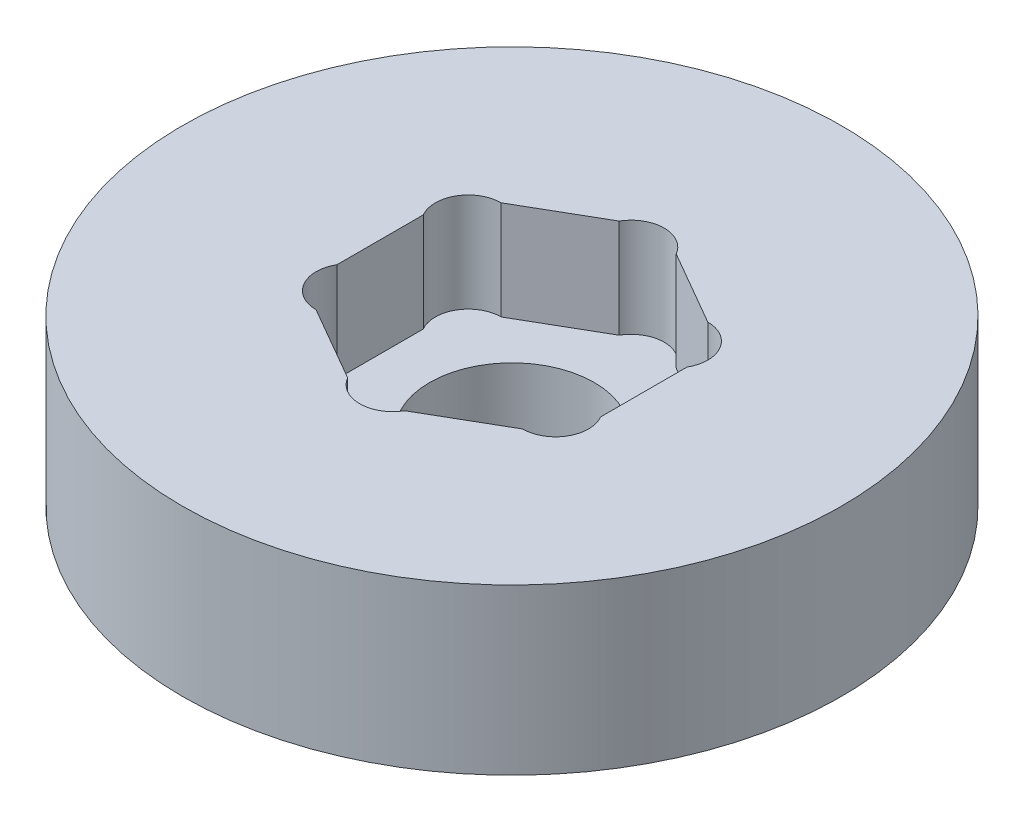
SolidWorks part; units mm, degrees
ref_plane "정면" through (0, 0, 0) normal (0, 0, 1) x (1, 0, 0)
ref_plane "윗면" through (0, 0, 0) normal (0, 1, 0) x (1, 0, 0)
ref_plane "우측면" through (0, 0, 0) normal (1, 0, 0) x (0, 0, -1)
sketch "스케치1" plane through (0, 0, 0) normal (0, 1, 0) x (1, 0, 0)
  circle A0 centre (0, 0) radius 10
  dimension "D1" = 20
extrude "보스-돌출1" add sketch "스케치1" along normal blind 5
sketch "스케치2" plane through (0, 5, 0) normal (0, 1, 0) x (1, 0, 0)
  line L1 (0, 4.6188) -> (-4, 2.3094)
  line L2 (-4, 2.3094) -> (-4, -2.3094)
  line L3 (-4, -2.3094) -> (0, -4.6188)
  line L4 (0, -4.6188) -> (4, -2.3094)
  line L5 (4, -2.3094) -> (4, 2.3094)
  line L6 (4, 2.3094) -> (0, 4.6188)
  circle A0 centre (0, 0) radius 4 construction
  dimension "D1" = 8
extrude "컷-돌출1" cut sketch "스케치2" against normal blind 3
sketch "스케치3" plane through (0, 5, 0) normal (0, 1, 0) x (1, 0, 0)
  line L0 (0, 0) -> (0, 3.6188) construction
  circle A0 centre (0, 3.6188) radius 1
  circle A1 centre (3.134, 1.8094) radius 1
  circle A2 centre (3.134, -1.8094) radius 1
  circle A3 centre (0, -3.6188) radius 1
  circle A4 centre (-3.134, -1.8094) radius 1
  circle A5 centre (-3.134, 1.8094) radius 1
  point P18 (0, 0)
  dimension "D1" = 2
  dimension "D2" = 6
extrude "컷-돌출2" cut sketch "스케치3" against normal blind 3
sketch "스케치5" plane through (0, 0, 0) normal (0, -1, 0) x (1, 0, 0)
  circle A0 centre (0, 0) radius 2.5
  dimension "D1" = 5
extrude "컷-돌출3" cut sketch "스케치5" against normal blind 3
